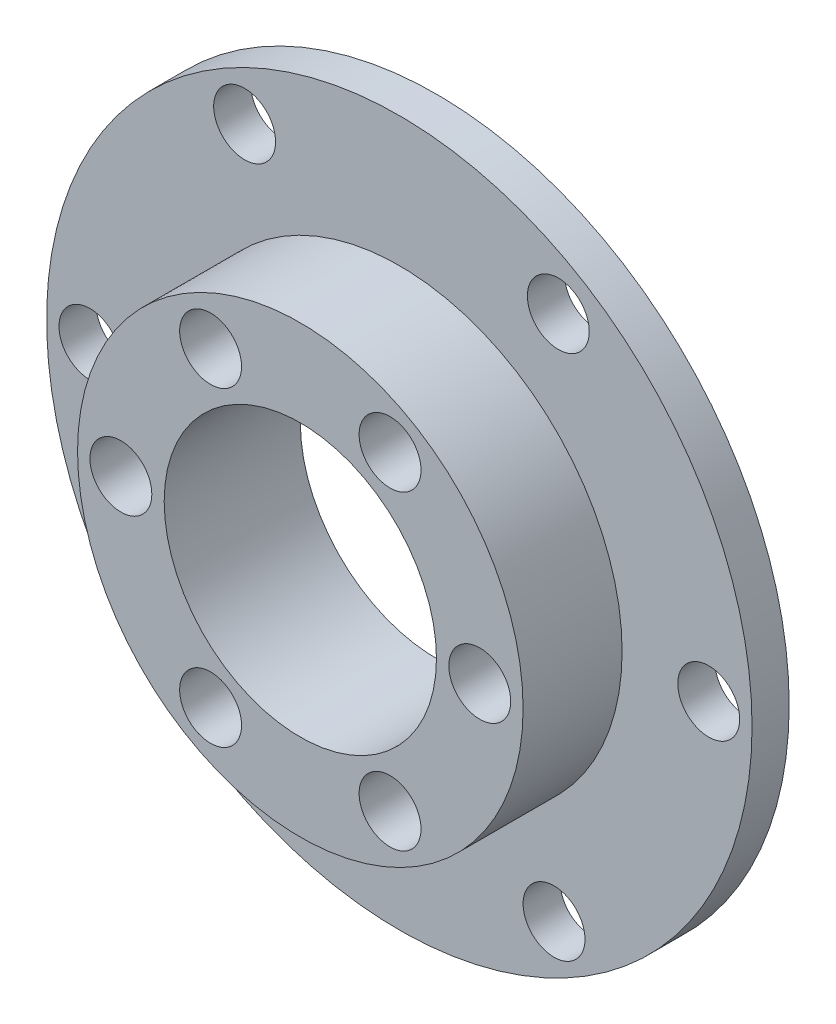
SolidWorks part; units mm, degrees
ref_plane "前视基准面" through (0, 0, 0) normal (0, 0, 1) x (1, 0, 0)
ref_plane "上视基准面" through (0, 0, 0) normal (0, 1, 0) x (1, 0, 0)
ref_plane "右视基准面" through (0, 0, 0) normal (1, 0, 0) x (0, 0, -1)
sketch "草图1" plane through (0, 0, 0) normal (0, 0, 1) x (1, 0, 0)
  circle A0 centre (0, 0) radius 11
  circle A1 centre (0, 0) radius 28.5
  circle A3 centre (-7.25, 12.5574) radius 2.5
  circle A4 centre (7.25, 12.5574) radius 2.5
  circle A5 centre (-14.5, 0) radius 2.5
  circle A6 centre (14.5, 0) radius 2.5
  circle A7 centre (7.25, -12.5574) radius 2.5
  circle A8 centre (-7.25, -12.5574) radius 2.5
  circle A9 centre (0, 0) radius 18
  circle A11 centre (-12.5, 21.6506) radius 2.5
  circle A12 centre (-25, 0) radius 2.5
  circle A13 centre (12.846, 21.0513) radius 2.5
  circle A14 centre (25, 0) radius 2.5
  circle A15 centre (12.5, -21.6506) radius 2.5
  circle A16 centre (-12.5, -21.6506) radius 2.5
extrude "凸台-拉伸3" add sketch "草图1" along normal blind 3 contours A1 A16 A15 A14 A13 A12 A11 A9 | A9 A0 A3 A4 A5 A6 A7 A8
sketch "草图3" plane through (0, 0, 3) normal (0, 0, 1) x (1, 0, 0)
  circle A0 centre (0, 0) radius 11
  circle A1 centre (0, 0) radius 18
  circle A2 centre (-14.5, 0) radius 2.5
  circle A3 centre (-7.25, 12.5574) radius 2.5
  circle A4 centre (7.25, 12.5574) radius 2.5
  circle A5 centre (14.5, 0) radius 2.5
  circle A6 centre (7.25, -12.5574) radius 2.5
  circle A7 centre (-7.25, -12.5574) radius 2.5
extrude "凸台-拉伸4" add sketch "草图3" along normal blind 8
